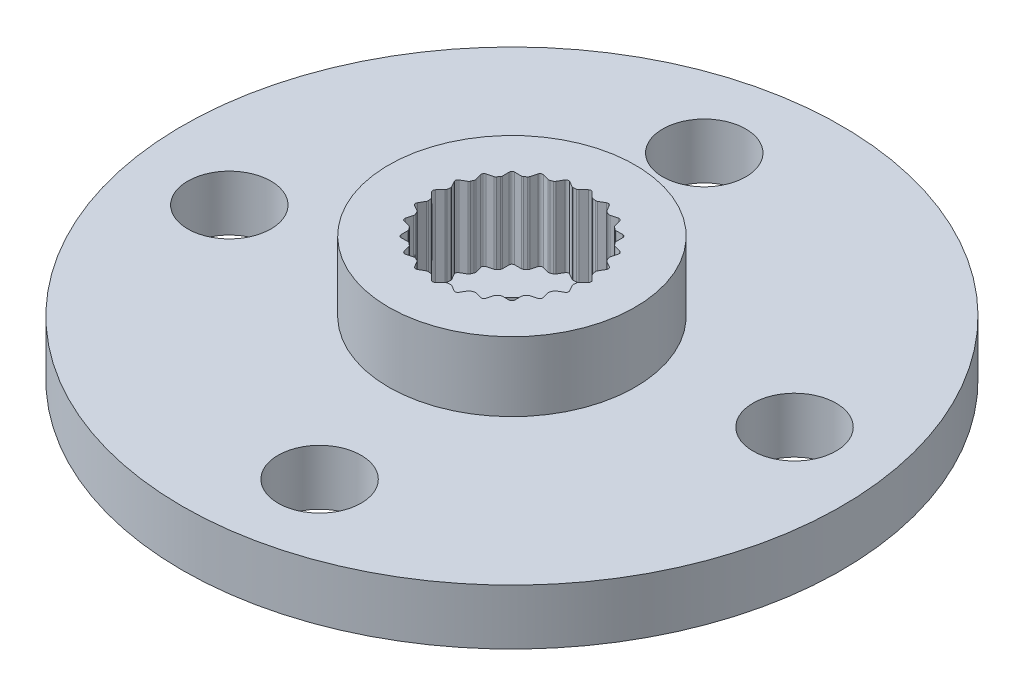
SolidWorks part; units mm, degrees
ref_plane "Спереди" through (0, 0, 0) normal (0, 0, 1) x (1, 0, 0)
ref_plane "Сверху" through (0, 0, 0) normal (0, 1, 0) x (1, 0, 0)
ref_plane "Справа" through (0, 0, 0) normal (1, 0, 0) x (0, 0, -1)
sketch "Эскиз1" plane through (0, 0, 0) normal (0, 1, 0) x (1, 0, 0)
  circle A0 centre (0, 0) radius 11.9
  dimension "D1" = 23.8
extrude "Бобышка-Вытянуть1" add sketch "Эскиз1" along normal blind 2
sketch "Эскиз2" plane through (0, 2, 0) normal (0, 1, 0) x (1, 0, 0)
  circle A0 centre (0, 0) radius 4.45
  dimension "D1" = 8.9
extrude "Бобышка-Вытянуть2" add sketch "Эскиз2" along normal blind 2.5
sketch "Эскиз3" plane through (0, 0, 0) normal (0, -1, 0) x (1, 0, 0)
  circle A0 centre (0, 0) radius 3.75
  dimension "D1" = 7.5
extrude "Бобышка-Вытянуть3" add sketch "Эскиз3" along normal blind 0.5
sketch "Эскиз4" plane through (0, -0.5, 0) normal (0, -1, 0) x (1, 0, 0)
  circle A0 centre (0, 0) radius 3
  dimension "D1" = 6
extrude "Вырез-Вытянуть1" cut sketch "Эскиз4" against normal blind 1
sketch "Эскиз5" plane through (0, 0.5, 0) normal (0, -1, 0) x (1, 0, 0)
  circle A0 centre (0, 0) radius 1.4
  dimension "D1" = 2.8
extrude "Вырез-Вытянуть2" cut sketch "Эскиз5" against normal through all
sketch "Эскиз6" plane through (0, 4.5, 0) normal (0, 1, 0) x (1, 0, 0)
  circle A0 centre (0, 0) radius 2.65
  dimension "D1" = 5.3
extrude "Вырез-Вытянуть3" cut sketch "Эскиз6" against normal blind 2.9
sketch "Эскиз7" plane through (0, 4.5, 0) normal (0, 1, 0) x (1, 0, 0)
  line L0 (0, 2.9) -> (-0.2631, 2.6369)
  line L1 (0, 2.9) -> (0.2631, 2.6369)
  line L2 (0, 2.9) -> (0, 0) construction
  circle A0 centre (0, 0) radius 2.65 construction
  arc A1 (-0.2631, 2.6369) -> (0.2631, 2.6369) centre (0, 0) cw
  circle A2 centre (0, 0) radius 2.65 construction
  circle A3 centre (0, 0) radius 2.9 construction
  dimension "D3" = 5.8
  dimension "D1" = 90
  dimension "D2" = 45
extrude "Вырез-Вытянуть4" cut sketch "Эскиз7" against normal up to surface (2.9 mm away) up to face at (0, 1.6, 2.65)
fillet "Скругление1" radius 0.1 3 edges at (0.2631, 3.05, -2.6369) (-0.2631, 3.05, -2.6369) (0, 3.05, -2.9)
pattern_circular "Круговой массив1" count 24 over 360 about axis through (0, 0, 0) along (0, 1, 0) of "Вырез-Вытянуть4", "Скругление1"
sketch "Эскиз8" plane through (0, 0, 0) normal (0, -1, 0) x (1, 0, 0)
  line L0 (0, 0) -> (0, 7) construction
  line L1 (0, 7) -> (0, 10) construction
  circle A0 centre (0, 0) radius 7 construction
  circle A1 centre (0, 0) radius 10 construction
  circle A2 centre (0, 10) radius 0.7
  circle A3 centre (0, 7) radius 0.7
  dimension "D1" = 20
  dimension "D2" = 14
  dimension "D3" = 1.4
extrude "Вырез-Вытянуть5" [suppressed] cut sketch "Эскиз8" against normal through all
pattern_circular "Круговой массив2" [suppressed] count 18 over 360
sketch "Эскиз10" [suppressed] plane through (0, 0, 0) normal (0, -1, 0) x (1, 0, 0)
  circle A0 centre (0, 0) radius 8.5 construction
  circle A1 centre (8.5, 0) radius 0.7
  circle A2 centre (0, 10) radius 0.7 construction
  dimension "D1" = 17
extrude "Вырез-Вытянуть6" [suppressed] cut sketch "Эскиз10" against normal through all
pattern_circular "Круговой массив3" [suppressed] count 18 over 360
sketch "Esquisse1" plane through (0, 0, 0) normal (0, -1, 0) x (1, 0, 0)
  circle A0 centre (-8.5742, 1.6296) radius 1.5
  dimension "D1" = 3
extrude "Enlèv. mat.-Extru.1" cut sketch "Esquisse1" against normal blind 10
pattern_circular "Répétition circulaire1" count 4 over 360 about axis through (0, 0, 0) along (0, 1, 0) of "Enlèv. mat.-Extru.1"
